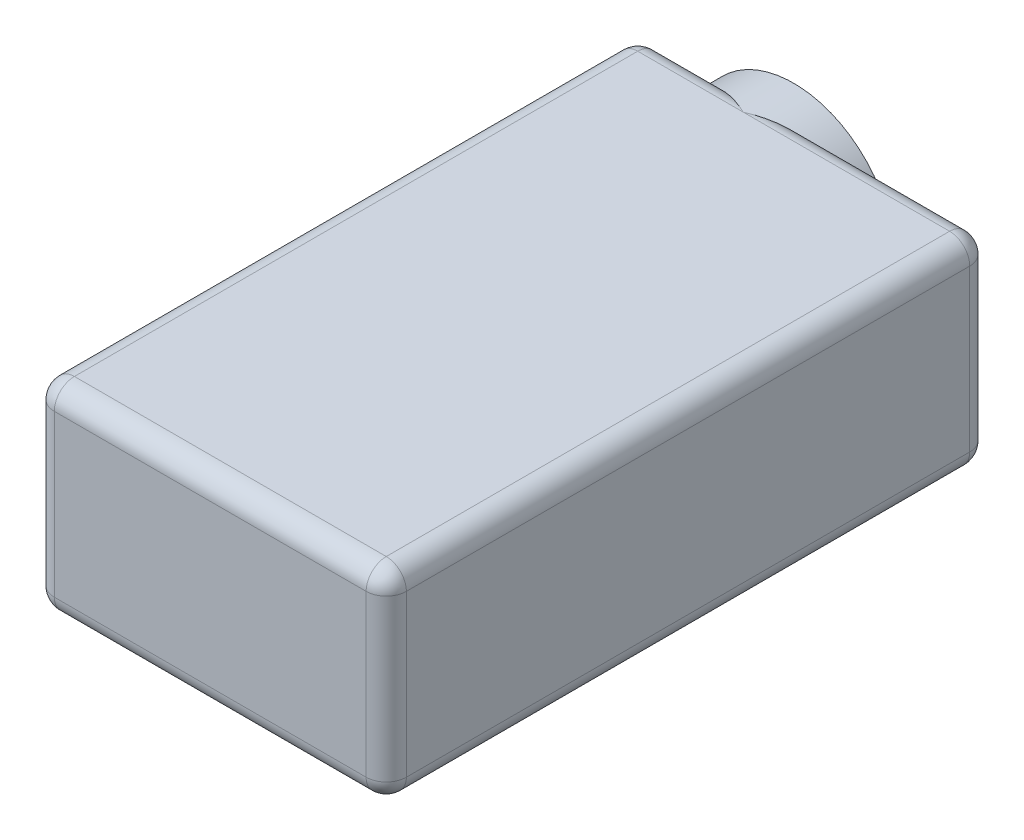
SolidWorks part; units mm, degrees
ref_plane "Front Plane" through (0, 0, 0) normal (0, 0, 1) x (1, 0, 0)
ref_plane "Top Plane" through (0, 0, 0) normal (0, 1, 0) x (1, 0, 0)
ref_plane "Right Plane" through (0, 0, 0) normal (1, 0, 0) x (0, 0, -1)
sketch "Sketch1" plane through (0, 0, 0) normal (0, 1, 0) x (1, 0, 0)
  line L1 (-17.5, -30) -> (17.5, -30)
  line L2 (-17.5, -30) -> (-17.5, 30)
  line L3 (-17.5, 30) -> (17.5, 30)
  line L4 (17.5, -30) -> (17.5, 30)
  line L5 (-17.5, -30) -> (17.5, 30) construction
  line L6 (-17.5, 30) -> (17.5, -30) construction
  point P0 (0, 0)
  dimension "D1" = 35
  dimension "D2" = 60
extrude "Boss-Extrude1" add sketch "Sketch1" along normal blind 20
fillet "Fillet1" radius 2 12 edges at (0, 0, -30) (-17.5, 10, -30) (-17.5, 0, 0) (-17.5, 10, 30) (0, 0, 30) (17.5, 10, 30) (17.5, 10, -30) (17.5, 0, 0) (0, 20, 30) (-17.5, 20, 0) (0, 20, -30) (17.5, 20, 0)
sketch "Sketch2" plane through (0, 0, -30) normal (0, 0, -1) x (-1, 0, 0)
  line L0 (15.5, 10) -> (-15.5, 10) construction
  line L1 (15.5, 2) -> (15.5, 18) construction
  line L2 (-15.5, 18) -> (-15.5, 2) construction
  circle A0 centre (5, 10) radius 10
  point P8 (0, 10)
  dimension "D2" = 20
  dimension "D1" = 5
extrude "Boss-Extrude2" add sketch "Sketch2" along normal blind 3 and the other way blind 3
sketch "Sketch3" plane through (0, 0, -33) normal (0, 0, -1) x (-1, 0, 0)
  circle A0 centre (5, 10) radius 6
  dimension "D1" = 12
extrude "Cut-Extrude1" cut sketch "Sketch3" against normal blind 1
